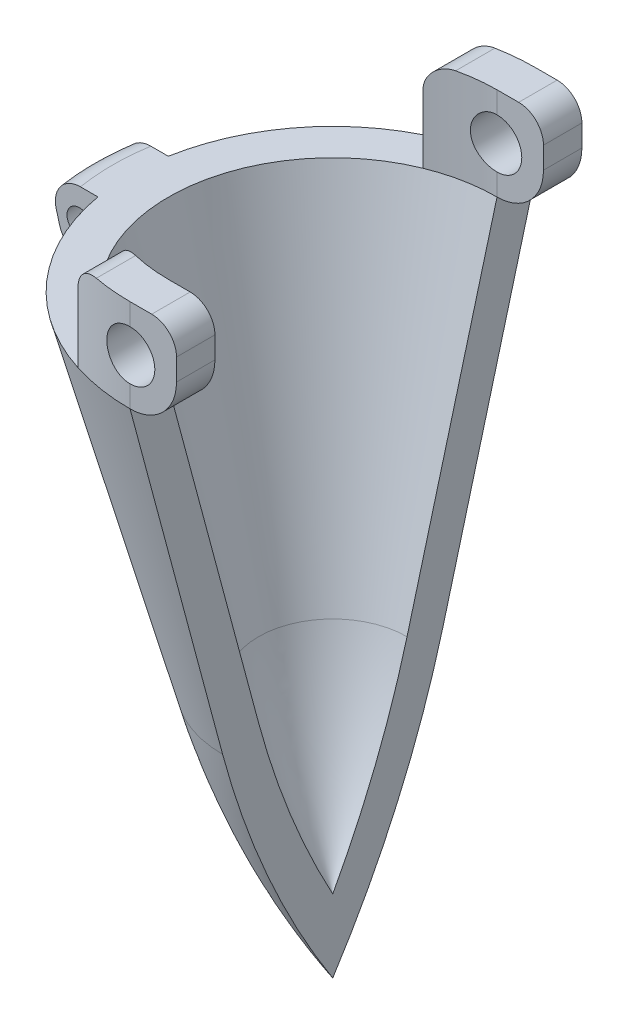
SolidWorks part; units mm, degrees
ref_plane "Alzado" through (0, 0, 0) normal (0, 0, 1) x (1, 0, 0)
ref_plane "Planta" through (0, 0, 0) normal (0, 1, 0) x (1, 0, 0)
ref_plane "Vista lateral" through (0, 0, 0) normal (1, 0, 0) x (0, 0, -1)
sketch "Croquis1" plane through (0, 0, 0) normal (1, 0, 0) x (0, 0, -1)
  line L1 (-17.7956, 40.1985) -> (-32.7475, 96)
  line L2 (-32.7475, 96) -> (-26.5359, 96)
  line L3 (-26.5359, 96) -> (-12, 41.7514)
  line L5 (0, 11.7514) -> (0, 0)
  line L6 (0, 0) -> (0, 62.8711) construction
  arc A0 (0, 0) -> (-17.7956, 40.1985) centre (119.7675, 77.0584) cw
  arc A1 (-12, 41.7514) -> (0, 11.7514) centre (119.7675, 77.0584) ccw
  dimension "D1" = 15
  dimension "D2" = 6
  dimension "D3" = 12
  dimension "D4" = 96
  dimension "D5" = 30
revolve "Revolución1" add sketch "Croquis1" angle 180 about L5
sketch "Croquis3" plane through (0, 96, 0) normal (0, 1, 0) x (1, 0, 0)
  line L0 (-10, -24.5795) -> (-10, -31.1833)
  line L3 (-10, 24.5795) -> (-10, 31.1833)
  line L4 (-46.5845, 0) -> (22.4461, 0) construction
  line L7 (0, -26.5359) -> (10, -26.5359)
  line L8 (10, -26.5359) -> (10, -32.7475)
  line L9 (10, -32.7475) -> (0, -32.7475)
  line L10 (10, 32.7475) -> (0, 32.7475)
  line L11 (10, 26.5359) -> (10, 32.7475)
  line L12 (0, 26.5359) -> (10, 26.5359)
  arc A0 (-10, -24.5795) -> (0, -26.5359) centre (0, 0) ccw
  arc A1 (0, 26.5359) -> (0, -26.5359) centre (0, 0) ccw construction
  arc A2 (-10, -31.1833) -> (0, -32.7475) centre (0, 0) ccw
  arc A3 (0, 32.7475) -> (0, -32.7475) centre (0, 0) ccw construction
  arc A6 (-10, 24.5795) -> (0, 26.5359) centre (0, 0) cw
  arc A7 (-10, 31.1833) -> (0, 32.7475) centre (0, 0) cw
  dimension "D1" = 6.2117
  dimension "D2" = 10
  dimension "D3" = 10
extrude "Saliente-Extruir1" add sketch "Croquis3" along normal blind 15
ref_plane "Plano1" through (0, 0, 32.7475) normal (0, 0, 1) x (1, 0, 0)
sketch "Croquis4" plane through (0, 0, 32.7475) normal (0, 0, 1) x (1, 0, 0)
  line L2 (-10, 96) -> (0, 96) construction
  line L4 (-10, 111) -> (-10, 96) construction
  circle A0 centre (0, 103.5) radius 4
  dimension "D1" = 8
  dimension "D2" = 7.5
  dimension "D3" = 10
extrude "Cortar-Extruir1" cut sketch "Croquis4" against normal through all
sketch "Croquis5" plane through (0, 0, 0) normal (0, 0, 1) x (1, 0, 0)
  line L0 (-32.7475, 96) -> (-40.7475, 96)
  line L1 (-40.7475, 96) -> (-38.068, 86)
  line L2 (-38.068, 86) -> (-30.068, 86)
  line L3 (-32.7475, 96) -> (-17.7956, 40.1985) construction
  line L4 (-30.068, 86) -> (-32.7475, 96)
  line L5 (0, 0) -> (0, 21.2258) construction
  line L6 (0, 0) -> (0, 40.1985) construction
  dimension "D1" = 8
  dimension "D2" = 10
revolve "Revolución2" add sketch "Croquis5" angle 10 about L5 other way angle 10
sketch "Croquis6" plane through (0, 96, 0) normal (0, 1, 0) x (1, 0, 0)
  line L0 (-32.25, 5.6865) -> (-40.3488, 5.6865)
  line L1 (-40.3488, 5.6865) -> (-40.1285, 7.0757)
  line L2 (-40.1285, 7.0757) -> (-32.25, 5.6865)
  line L3 (-32.25, -5.6865) -> (-40.3488, -5.6865)
  line L4 (-40.3488, -5.6865) -> (-40.1285, -7.0757)
  line L5 (-40.1285, -7.0757) -> (-32.25, -5.6865)
  arc A0 (-40.1285, 7.0757) -> (-40.1285, -7.0757) centre (0, 0) ccw construction
extrude "Cortar-Extruir2" cut sketch "Croquis6" against normal blind 10
sketch "Croquis7" plane through (0, 0, 5.6865) normal (0, 0, 1) x (1, 0, 0)
  line L0 (-32.25, 86) -> (-37.6409, 86) construction
  circle A0 centre (-35.25, 91) radius 2
  dimension "D3" = 4
  dimension "D1" = 5
  dimension "D2" = 3
extrude "Cortar-Extruir3" cut sketch "Croquis7" against normal through all
sketch "Croquis8" plane through (0, 0, 32.7475) normal (0, 0, 1) x (1, 0, 0)
  line L2 (7.5, 103.5) -> (7.5, 111)
  line L3 (0, 111) -> (10, 111) construction
  line L4 (7.5, 111) -> (10, 111)
  line L5 (10, 111) -> (10, 96)
  line L6 (10, 96) -> (0, 96)
  arc A0 (0, 96) -> (7.5, 103.5) centre (0, 103.5) ccw
extrude "Cortar-Extruir4" cut sketch "Croquis8" against normal through all
fillet "Redondeo1" radius 4 6 edges at (7.5, 111, -29.6417) (7.5, 111, 29.6417) (-10, 111, -27.8814) (-10, 111, 27.8814) (-38.068, 86, 0)
